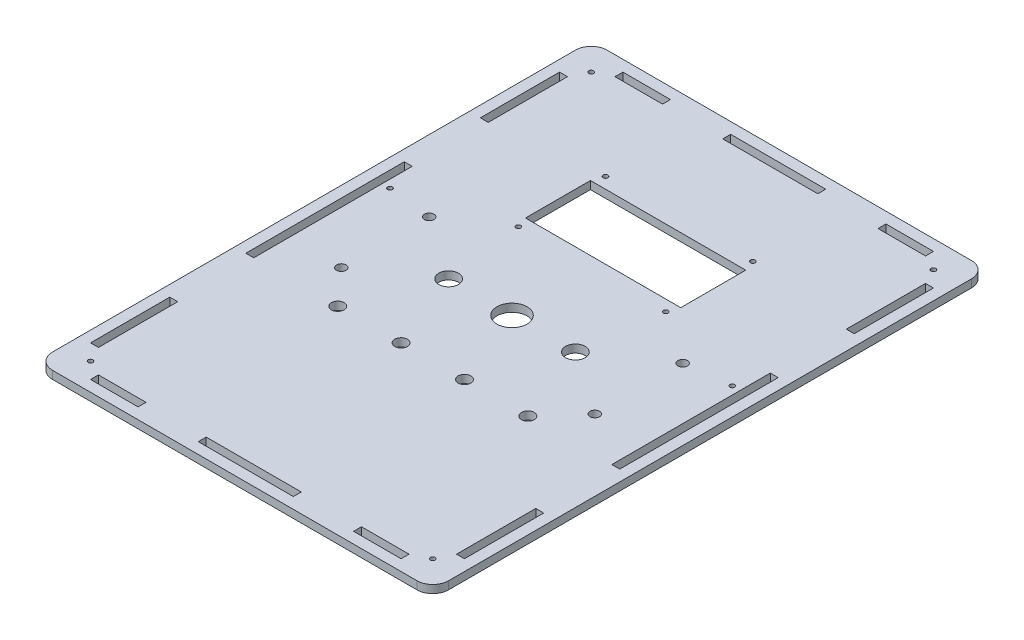
SolidWorks part; units mm, degrees
ref_plane "Front Plane" through (0, 0, 0) normal (0, 0, 1) x (1, 0, 0)
ref_plane "Top Plane" through (0, 0, 0) normal (0, 1, 0) x (1, 0, 0)
ref_plane "Right Plane" through (0, 0, 0) normal (1, 0, 0) x (0, 0, -1)
sketch "Sketch1" plane through (0, 0, 0) normal (0, 1, 0) x (1, 0, 0)
  line L0 (125, 350) -> (125, 0) construction
  line L1 (10, 0) -> (240, 0)
  line L2 (0, 10) -> (0, 340)
  line L3 (10, 350) -> (240, 350)
  line L4 (250, 10) -> (250, 340)
  line L5 (0, 175) -> (250, 175) construction
  line L13 (57, 343) -> (27, 343)
  line L14 (125, 343) -> (95, 343)
  line L15 (7, 323) -> (12, 323)
  line L16 (7, 323) -> (7, 273)
  line L17 (7, 273) -> (12, 273)
  line L18 (12, 323) -> (12, 273)
  line L19 (7, 225) -> (12, 225)
  line L20 (7, 225) -> (7, 175)
  line L22 (12, 225) -> (12, 125)
  line L23 (95, 343) -> (95, 338)
  line L24 (95, 338) -> (155, 338)
  line L25 (27, 343) -> (27, 338)
  line L26 (27, 338) -> (57, 338)
  line L27 (57, 338) -> (57, 343)
  line L28 (95, 12) -> (155, 12)
  line L29 (95, 7) -> (95, 12)
  line L30 (57, 12) -> (57, 7)
  line L31 (27, 12) -> (57, 12)
  line L32 (27, 7) -> (27, 12)
  line L33 (7, 77) -> (12, 77)
  line L34 (12, 27) -> (12, 77)
  line L35 (7, 27) -> (12, 27)
  line L36 (7, 125) -> (12, 125)
  line L37 (155, 7) -> (155, 12)
  line L38 (193, 12) -> (193, 7)
  line L39 (223, 7) -> (223, 12)
  line L40 (223, 12) -> (193, 12)
  line L41 (243, 27) -> (238, 27)
  line L42 (238, 27) -> (238, 77)
  line L43 (243, 77) -> (238, 77)
  line L44 (243, 125) -> (238, 125)
  line L45 (238, 225) -> (238, 125)
  line L46 (243, 225) -> (238, 225)
  line L47 (243, 273) -> (238, 273)
  line L48 (238, 323) -> (238, 273)
  line L49 (243, 323) -> (238, 323)
  line L50 (223, 343) -> (223, 338)
  line L51 (223, 338) -> (193, 338)
  line L52 (193, 338) -> (193, 343)
  line L53 (155, 343) -> (155, 338)
  line L54 (155, 343) -> (125, 343)
  line L55 (193, 343) -> (223, 343)
  line L56 (243, 323) -> (243, 273)
  line L57 (243, 225) -> (243, 125)
  line L58 (243, 77) -> (243, 27)
  line L59 (223, 7) -> (193, 7)
  line L60 (155, 7) -> (95, 7)
  line L61 (27, 7) -> (57, 7)
  line L62 (7, 27) -> (7, 77)
  line L63 (7, 175) -> (7, 125)
  line L81 (174, 232.5) -> (76, 232.5)
  line L82 (174, 232.5) -> (174, 273.5)
  line L83 (174, 273.5) -> (76, 273.5)
  line L84 (76, 232.5) -> (76, 273.5)
  arc A12 (0, 10) -> (10, 0) centre (10, 10) ccw
  arc A13 (240, 0) -> (250, 10) centre (240, 10) ccw
  arc A14 (250, 340) -> (240, 350) centre (240, 340) ccw
  arc A15 (0, 340) -> (10, 350) centre (10, 340) cw
  circle A16 centre (78.5, 280.5) radius 1.5
  circle A17 centre (171.5, 280.5) radius 1.5
  circle A18 centre (171.5, 225.5) radius 1.5
  circle A19 centre (78.5, 225.5) radius 1.5
  circle A20 centre (125, 175) radius 9.5
  circle A21 centre (85, 175) radius 6.2
  circle A22 centre (165, 175) radius 6.2
  circle A23 centre (45, 202.7339) radius 3
  circle A24 centre (45, 147.2661) radius 3
  circle A25 centre (205, 147.2661) radius 3
  circle A26 centre (205, 202.7339) radius 3
  circle A27 centre (105, 125) radius 4
  circle A28 centre (65, 125) radius 4
  circle A29 centre (185, 125) radius 4
  circle A30 centre (145, 125) radius 4
  circle A31 centre (17, 333) radius 1.5
  circle A32 centre (17, 206) radius 1.5
  circle A34 centre (17, 17) radius 1.5
  circle A35 centre (233, 333) radius 1.5
  circle A36 centre (233, 206) radius 1.5
  circle A38 centre (233, 17) radius 1.5
  point P9 (0, 0)
  point P12 (125, 236.48)
  point P13 (125, 333)
  point P14 (250, 0)
  point P19 (0, 350)
  point P28 (125, 252)
  point P33 (125, 175)
  point P36 (125, 252)
  point P37 (125, 252)
  point P68 (12, 175)
  point P72 (125, 12)
  point P94 (125, 338)
  dimension "D6" = 12.4
  dimension "D7" = 6
  dimension "D3" = 10
  dimension "D8" = 41
  dimension "D11" = 40
  dimension "D12" = 40
  dimension "D10" = 12.4
  dimension "D13" = 6
  dimension "D14" = 19
  dimension "D26" = 20
  dimension "D28" = 17
  dimension "D30" = 31
  dimension "D1" = 350
  dimension "D2" = 250
  dimension "D4" = 93
  dimension "D5" = 55
  dimension "D9" = 98
  dimension "D15" = 76
  dimension "D16" = 5
  dimension "D17" = 76
  dimension "D18" = 50
  dimension "D19" = 5
  dimension "D20" = 50
  dimension "D21" = 57.5
  dimension "D22" = 30
  dimension "D23" = 5
  dimension "D24" = 5
  dimension "D25" = 30
  dimension "D27" = 40
  dimension "D29" = 17
  dimension "D31" = 5
  dimension "D32" = 55
  dimension "D33" = 93
extrude "Boss-Extrude1" add sketch "Sketch1" along normal blind 5
